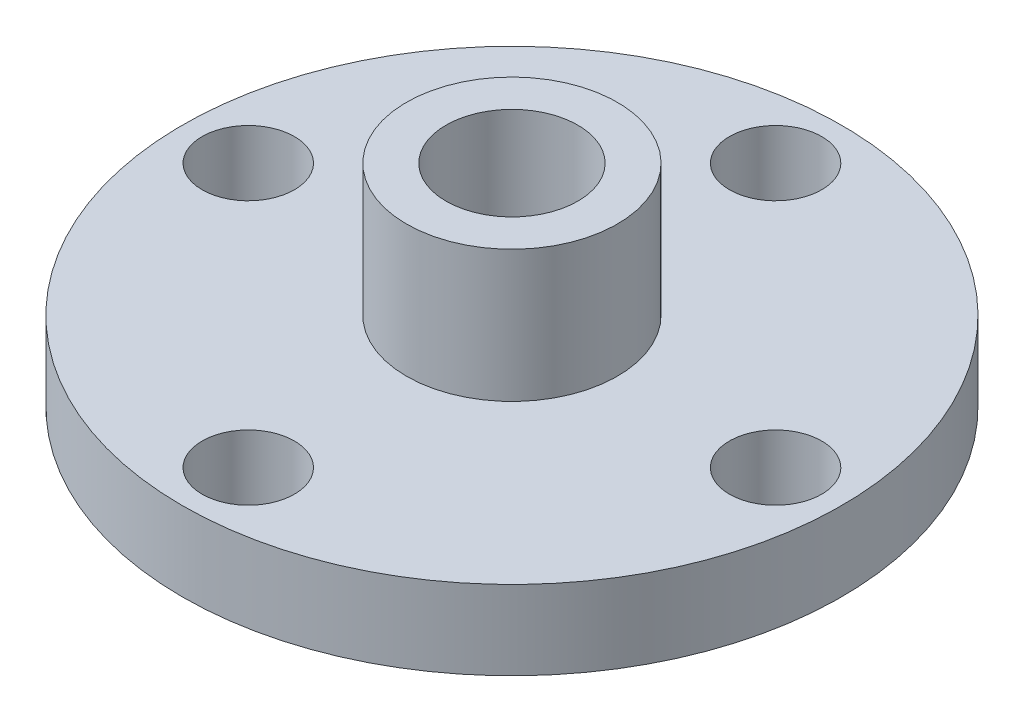
SolidWorks part; units mm, degrees
ref_plane "前视基准面" through (0, 0, 0) normal (0, 0, 1) x (1, 0, 0)
ref_plane "上视基准面" through (0, 0, 0) normal (0, 1, 0) x (1, 0, 0)
ref_plane "右视基准面" through (0, 0, 0) normal (1, 0, 0) x (0, 0, -1)
sketch "草图1" plane through (0, 0, 0) normal (0, 1, 0) x (1, 0, 0)
  circle A0 centre (0, 0) radius 2.5
  circle A1 centre (0, 0) radius 12.5
  circle A2 centre (0, 0) radius 10 construction
  circle A3 centre (0, 10) radius 1.75
  circle A4 centre (10, 0) radius 1.75
  circle A5 centre (0, -10) radius 1.75
  circle A6 centre (-10, 0) radius 1.75
  point P16 (0, 0)
  dimension "D1" = 5
  dimension "D2" = 25
  dimension "D3" = 20
  dimension "D4" = 3.5
  dimension "D5" = 4
extrude "凸台-拉伸1" add sketch "草图1" along normal blind 3
ref_plane "基准面1" through (0, 3, 0) normal (0, 1, 0) x (1, 0, 0)
sketch "草图2" plane through (0, 3, 0) normal (0, 1, 0) x (1, 0, 0)
  circle A0 centre (0, 0) radius 2.5
  circle A1 centre (0, 0) radius 4
  dimension "D1" = 8
extrude "凸台-拉伸2" add sketch "草图2" along normal blind 5
